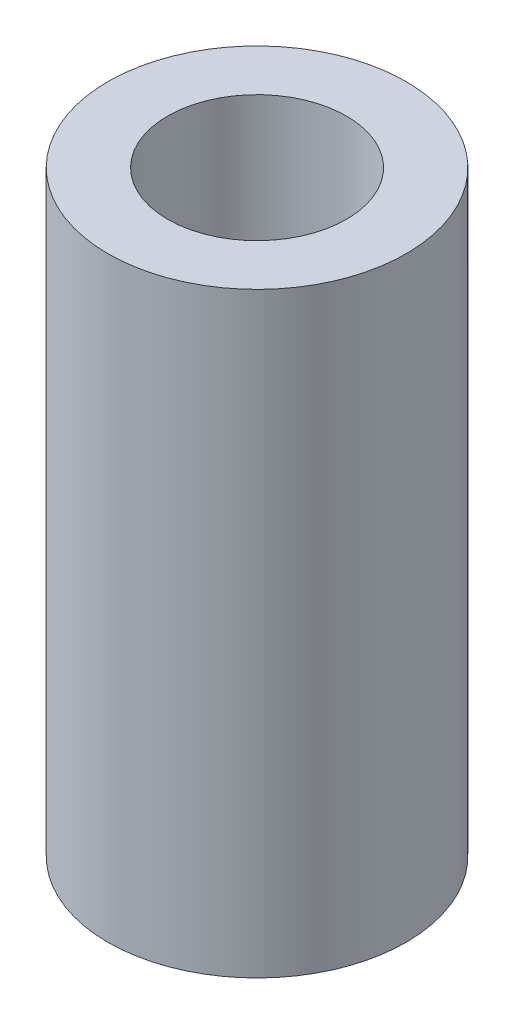
SolidWorks part; units mm, degrees
ref_plane "Спереди" through (0, 0, 0) normal (0, 0, 1) x (1, 0, 0)
ref_plane "Сверху" through (0, 0, 0) normal (0, 1, 0) x (1, 0, 0)
ref_plane "Справа" through (0, 0, 0) normal (1, 0, 0) x (0, 0, -1)
sketch "Sketch1" plane through (0, 0, 0) normal (0, 1, 0) x (1, 0, 0)
  circle A0 centre (-4.1871, 0.8374) radius 2
  circle A1 centre (-4.1871, 0.8374) radius 1.2
  dimension "D1" = 4
  dimension "D2" = 2.4
extrude "Boss-Extrude1" add sketch "Sketch1" along normal blind 8
